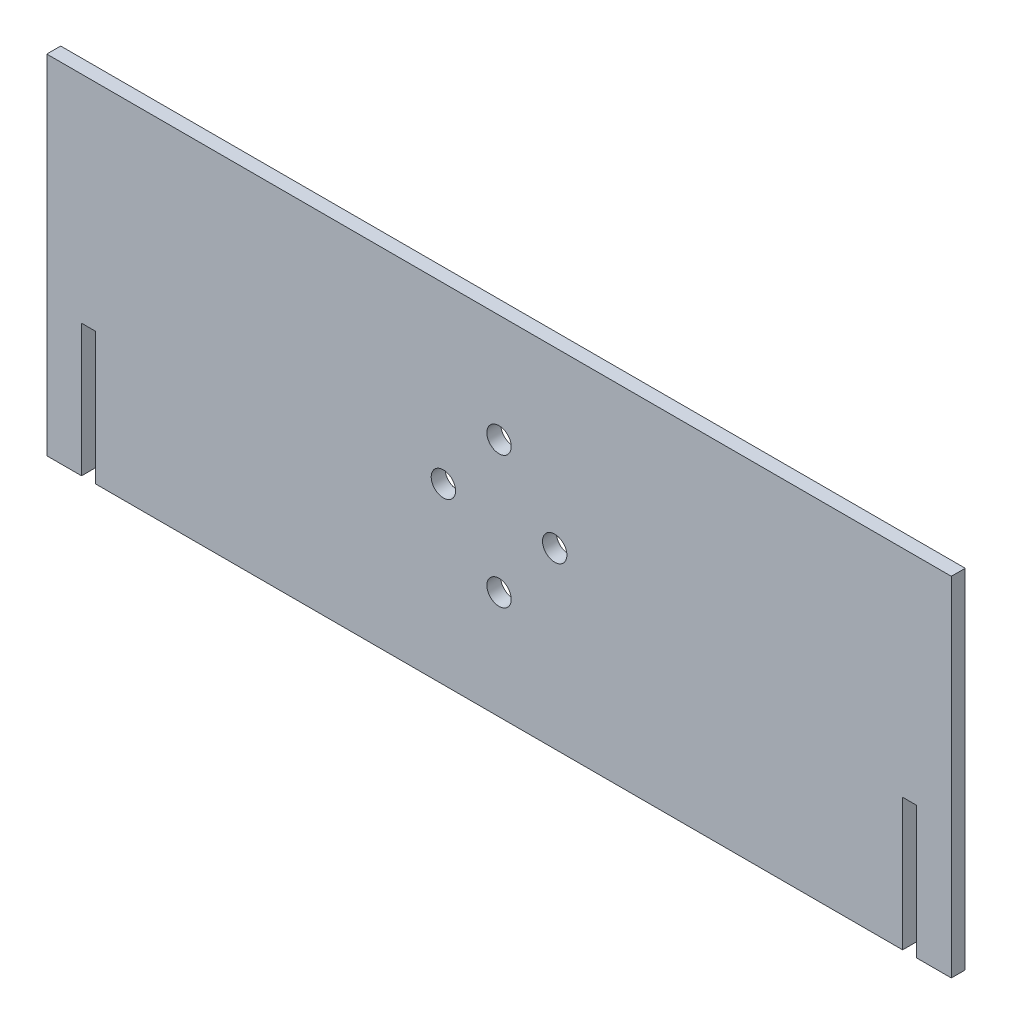
SolidWorks part; units mm, degrees
ref_plane "Front Plane" through (0, 0, 0) normal (0, 0, 1) x (1, 0, 0)
ref_plane "Top Plane" through (0, 0, 0) normal (0, 1, 0) x (1, 0, 0)
ref_plane "Right Plane" through (0, 0, 0) normal (1, 0, 0) x (0, 0, -1)
sketch "Sketch1" plane through (0, 0, 0) normal (0, 0, 1) x (1, 0, 0)
  line L0 (0, 40.669) -> (0, -42.4022) construction
  line L1 (-65, 25) -> (65, 25)
  line L2 (-65, 25) -> (-65, -25)
  line L3 (-65, -25) -> (-60, -25)
  line L4 (65, 25) -> (65, -25)
  line L5 (-65, 25) -> (65, -25) construction
  line L6 (-65, -25) -> (65, 25) construction
  line L7 (-73.0432, 0) -> (78.8619, 0) construction
  line L9 (58, -6) -> (60, -6)
  line L10 (58, -6) -> (58, -25)
  line L12 (60, -6) -> (60, -25)
  line L13 (-60, -6) -> (-60, -25)
  line L14 (-58, -6) -> (-58, -25)
  line L15 (-58, -6) -> (-60, -6)
  line L16 (60, -25) -> (65, -25)
  line L17 (-58, -25) -> (58, -25)
  circle A0 centre (0, 9.5) radius 1.75
  circle A1 centre (8, 0) radius 1.75
  circle A2 centre (0, -9.5) radius 1.75
  circle A3 centre (-8, 0) radius 1.75
  ellipse E0 centre (0, 0) end of major axis (0, -9.5) minor radius 8 construction
  point P0 (0, 0)
  dimension "D8" = 3.5
  dimension "D1" = 130
  dimension "D2" = 50
  dimension "D3" = 5
  dimension "D4" = 19
  dimension "D5" = 2
  dimension "D6" = 16
  dimension "D7" = 19
extrude "Boss-Extrude1" add sketch "Sketch1" along normal mid plane 2
